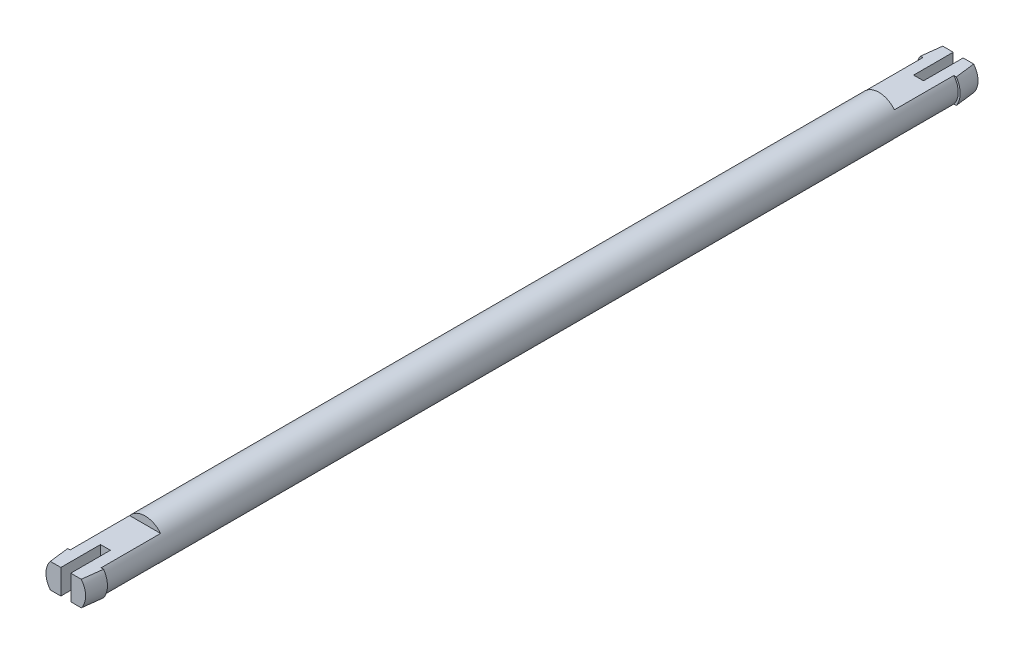
SolidWorks part; units mm, degrees
ref_plane "前视基准面" through (0, 0, 0) normal (0, 0, 1) x (1, 0, 0)
ref_plane "上视基准面" through (0, 0, 0) normal (0, 1, 0) x (1, 0, 0)
ref_plane "右视基准面" through (0, 0, 0) normal (1, 0, 0) x (0, 0, -1)
sketch "草图1" plane through (0, 0, 0) normal (0, 0, 1) x (1, 0, 0)
  circle A0 centre (0, 0) radius 2
extrude "凸台-拉伸1" add sketch "草图1" against normal blind 90
sketch "草图2" plane through (0, 0, 0) normal (0, 1, 0) x (1, 0, 0)
  line L0 (0, 0) -> (0, 2)
  line L1 (0, 2) -> (2.2, 2)
  line L2 (0, 0) -> (2, 0)
  line L3 (2, 0) -> (2.2, 2)
  dimension "D1" = 2.2
  dimension "D2" = 2
revolve "旋转1" add sketch "草图2" angle 360 about L0
sketch "草图3" plane through (0, 0, 0) normal (0, 0, 1) x (1, 0, 0)
  line L0 (-2.1, 1.25) -> (-2.1, 2.25)
  line L1 (-2.1, 1.25) -> (2.1, 1.25)
  line L2 (2.1, 1.25) -> (2.1, 2.25)
  line L3 (-2.1, -1.25) -> (2.1, -1.25)
  line L5 (-2.1, -2.25) -> (2.1, -2.25)
  line L6 (-2.1, -2.25) -> (-2.1, -1.25)
  line L7 (-2.1, 2.25) -> (2.1, 2.25)
  line L8 (2.1, -2.25) -> (2.1, -1.25)
  dimension "D1" = 1.25
  dimension "D2" = 1.25
  dimension "D3" = 1
  dimension "D4" = 1
extrude "切除-拉伸1" cut sketch "草图3" against normal blind 8
sketch "草图4" plane through (0, -1.25, 0) normal (0, -1, 0) x (1, 0, 0)
  line L0 (1.5612, 0) -> (-1.5612, 0) construction
  line L1 (-0.5, 0) -> (0.5, 0)
  line L2 (-0.5, 0) -> (-0.5, -4)
  line L3 (-0.5, -4) -> (0.5, -4)
  line L4 (0.5, 0) -> (0.5, -4)
extrude "切除-拉伸2" cut sketch "草图4" against normal up to next
sketch "草图5" plane through (0, 0, 0) normal (0, 1, 0) x (1, 0, 0)
  line L0 (0, 90) -> (0, 88)
  line L1 (2, 90) -> (-2, 90) construction
  line L2 (0, 88) -> (2.2, 88)
  line L3 (2.2, 88) -> (2, 90)
  line L4 (2, 90) -> (0, 90)
  line L5 (0, 58.1377) -> (0, 60.3241) construction
  dimension "D1" = 2.2
  dimension "D2" = 2
revolve "旋转2" add sketch "草图5" angle 360 about L5
sketch "草图6" plane through (0, 0, -90) normal (0, 0, -1) x (-1, 0, 0)
  line L1 (-2.1, 1.25) -> (2.1, 1.25)
  line L2 (-2.1, 1.25) -> (-2.1, 2.25)
  line L3 (-2.1, 2.25) -> (2.1, 2.25)
  line L4 (2.1, 1.25) -> (2.1, 2.25)
  line L5 (-2.1, -1.25) -> (2.1, -1.25)
  line L6 (-2.1, -1.25) -> (-2.1, -2.25)
  line L7 (-2.1, -2.25) -> (2.1, -2.25)
  line L8 (2.1, -1.25) -> (2.1, -2.25)
  dimension "D1" = 1.25
  dimension "D2" = 1.25
  dimension "D3" = 1
  dimension "D4" = 1
extrude "切除-拉伸3" cut sketch "草图6" against normal blind 8
sketch "草图7" plane through (0, 1.25, 0) normal (0, 1, 0) x (1, 0, 0)
  line L0 (0, 90) -> (0, 86) construction
  line L1 (-1.5612, 90) -> (1.5612, 90) construction
  line L2 (-0.5, 86) -> (0.5, 86)
  line L3 (0.5, 86) -> (0.5, 90)
  line L4 (0.5, 90) -> (-0.5, 90)
  line L5 (-0.5, 86) -> (-0.5, 90)
  dimension "D1" = 4
  dimension "D2" = 0.5
extrude "切除-拉伸4" cut sketch "草图7" against normal through all
